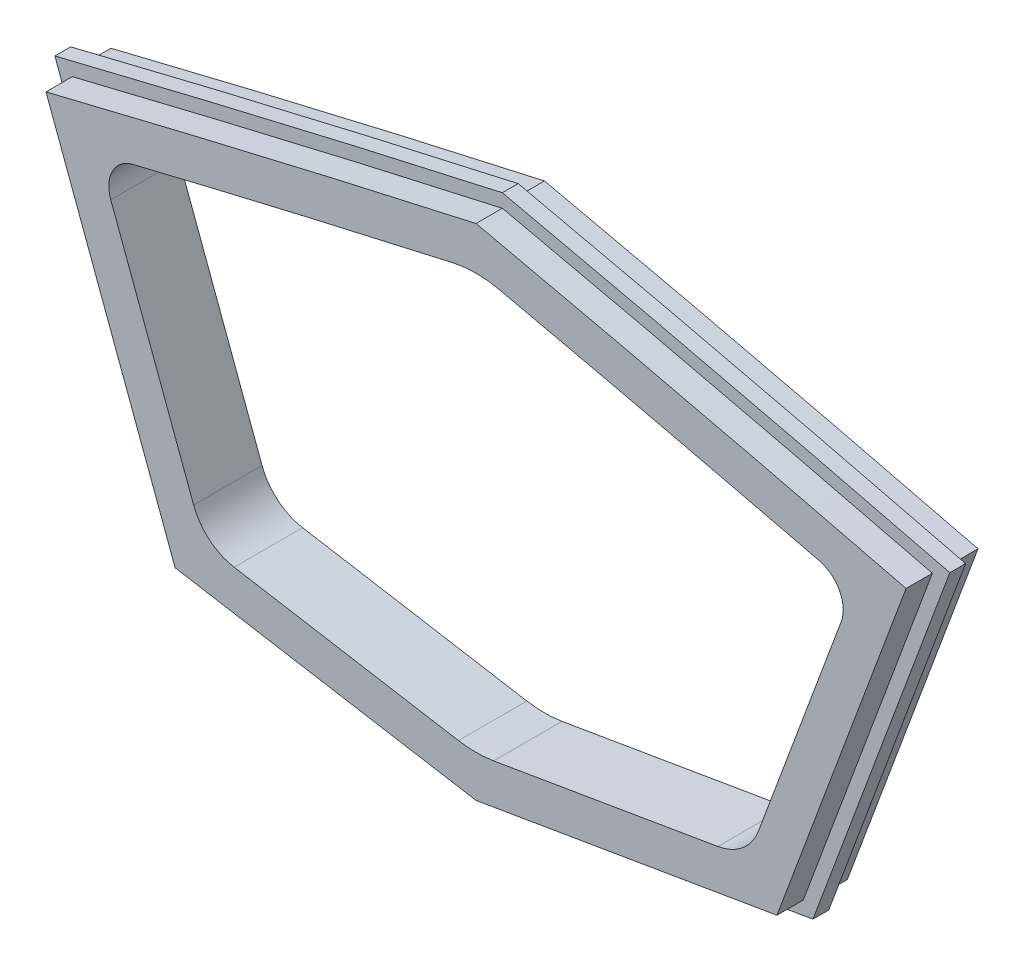
SolidWorks part; units mm, degrees
material "ABS"
ref_plane "Front Plane" through (0, 0, 0) normal (0, 0, 1) x (1, 0, 0)
ref_plane "Top Plane" through (0, 0, 0) normal (0, 1, 0) x (1, 0, 0)
ref_plane "Right Plane" through (0, 0, 0) normal (1, 0, 0) x (0, 0, -1)
sketch "Sketch1" plane through (0, 0, 0) normal (0, 0, 1) x (1, 0, 0)
  line L0 (51.6321, -61.1055) -> (71.7233, -7.0229)
  line L1 (-71.7233, -7.0229) -> (-51.6321, -61.1055)
  line L2 (-51.6321, -61.1055) -> (0, -69.8574)
  line L3 (0, -69.8574) -> (51.6321, -61.1055)
  line L8 (58.9956, -70) -> (85, 0.0001)
  line L9 (0, -80) -> (58.9956, -70)
  line L10 (-58.9956, -70) -> (0, -80)
  line L11 (-85, 0.0001) -> (-58.9956, -70)
  spline S0 degree 1 poles (71.7233, -7.0229) (0, 9.7572) knots 0 0 1 1 construction
  spline S1 degree 1 poles (0, 9.7572) (-71.7233, -7.0229) knots 0 0 1 1 construction
  spline S4 degree 3 poles (0, 19.9999) (-28.4207, 13.7115) (-56.7505, 7.0175) (-85, 0.0001) knots 0 0 0 0 1 1 1 1
  spline S5 degree 3 poles (85, 0.0001) (56.7505, 7.0175) (28.4208, 13.7115) (0, 19.9999) knots 0 0 0 0 1 1 1 1
  spline S6 degree 3 poles (71.7233, -7.0229) (65.7602, -5.5606) (53.8262, -2.6655) (35.9064, 1.5822) (17.9654, 5.7307) (5.9913, 8.427) (0, 9.7572) knots 0.128509 0.128509 0.128509 0.128509 0.340026 0.551543 0.76306 0.974577 0.974577 0.974577 0.974577
  spline S7 degree 3 poles (0, 9.7572) (-5.9913, 8.427) (-17.9654, 5.7308) (-35.9064, 1.5822) (-53.8262, -2.6654) (-65.7603, -5.5605) (-71.7233, -7.0229) knots 0.025423 0.025423 0.025423 0.025423 0.23694 0.448457 0.659974 0.871491 0.871491 0.871491 0.871491
  dimension "D2" = 10
extrude "Boss-Extrude1" add sketch "Sketch1" along normal blind 3
fillet "Fillet1" radius 20 2 edges at (0, -69.8574, 1.5) (0, 9.7572, 1.5)
fillet "Fillet2" radius 10 2 edges at (51.6321, -61.1055, 1.5) (-51.6321, -61.1055, 1.5)
fillet "Fillet3" radius 6 2 edges at (71.7233, -7.0229, 1.5) (-71.7233, -7.0229, 1.5)
sketch "Sketch2" plane through (0, 0, 3) normal (0, 0, 1) x (1, 0, 0)
  line L4 (-69.376, -13.3415) -> (-53.6427, -55.6934) construction
  line L5 (-45.9398, -62.0704) -> (-3.3424, -69.2908) construction
  line L6 (3.3424, -69.2908) -> (45.9398, -62.0704) construction
  line L7 (53.6427, -55.6934) -> (69.376, -13.3416) construction
  line L8 (-81.682, -1.7527) -> (-57.1548, -67.7764)
  line L9 (-57.1548, -67.7764) -> (0, -77.4643)
  line L10 (0, -77.4643) -> (57.1548, -67.7764)
  line L11 (57.1548, -67.7764) -> (81.6819, -1.7527)
  line L12 (-81.682, -1.7527) -> (-57.1548, -67.7764)
  line L13 (-57.1548, -67.7764) -> (0, -77.4643)
  line L14 (0, -77.4643) -> (57.1548, -67.7764)
  line L15 (57.1548, -67.7764) -> (81.6819, -1.7527)
  line L16 (-69.376, -13.3415) -> (-53.6427, -55.6934)
  line L17 (-45.9398, -62.0704) -> (-3.3424, -69.2908)
  line L18 (3.3424, -69.2908) -> (45.9398, -62.0704)
  line L19 (53.6427, -55.6934) -> (69.376, -13.3416)
  arc A1 (-65.1699, -5.4221) -> (-69.376, -13.3415) centre (-63.7516, -11.2521) ccw construction
  arc A2 (-53.6427, -55.6934) -> (-45.9398, -62.0704) centre (-44.2686, -52.211) ccw construction
  arc A3 (-3.3424, -69.2908) -> (3.3424, -69.2908) centre (0, -49.5721) ccw construction
  arc A4 (45.9398, -62.0704) -> (53.6427, -55.6934) centre (44.2686, -52.211) ccw construction
  arc A5 (69.376, -13.3416) -> (65.1699, -5.4222) centre (63.7515, -11.2521) ccw construction
  arc A6 (4.3632, 8.7852) -> (-4.3632, 8.7852) centre (0, -10.7331) ccw construction
  arc A7 (-65.1699, -5.4221) -> (-69.376, -13.3415) centre (-63.7516, -11.2521) ccw
  arc A8 (-53.6427, -55.6934) -> (-45.9398, -62.0704) centre (-44.2686, -52.211) ccw
  arc A9 (-3.3424, -69.2908) -> (3.3424, -69.2908) centre (0, -49.5721) ccw
  arc A10 (45.9398, -62.0704) -> (53.6427, -55.6934) centre (44.2686, -52.211) ccw
  arc A11 (69.376, -13.3416) -> (65.1699, -5.4222) centre (63.7515, -11.2521) ccw
  arc A12 (4.3632, 8.7852) -> (-4.3632, 8.7852) centre (0, -10.7331) ccw
  spline S3 degree 3 poles (2856.2231, -710.7914) (1223.1942, 104.564) (579.2853, 143.8341) (-35.9064, 1.5822) (-1030.2564, -234.1159) (-1933.2229, -901.7007) (1099.9889, 2490.3845) knots -21.098589 -21.098589 -21.098589 -21.098589 0.23694 0.448457 0.659974 35.447452 35.447452 35.447452 35.447452 only from (-4.3632, 8.7852) to (-65.1699, -5.4221) construction
  spline S4 degree 3 poles (3213.9817, 1579.7272) (901.2899, -2961.498) (-164.1911, 3027.1999) (-2889.2123, -2307.1163) knots -36.346529 -36.346529 -36.346529 -36.346529 30.527536 30.527536 30.527536 30.527536 only from (81.6819, -1.7527) to (0, 17.4394)
  spline S5 degree 3 poles (2884.6712, -2310.9837) (170.5811, 3032.8885) (-910.5565, -2969.0724) (-3206.0132, 1587.7256) knots -29.53804 -29.53804 -29.53804 -29.53804 37.373414 37.373414 37.373414 37.373414 only from (0, 17.4394) to (-81.682, -1.7527)
  spline S6 degree 3 poles (81.6819, -1.7527) (54.5322, 4.9703) (27.3082, 11.392) (0, 17.4394) knots 0 0 0 0 1 1 1 1
  spline S7 degree 3 poles (0, 17.4394) (-27.3081, 11.392) (-54.5323, 4.9703) (-81.682, -1.7527) knots 0 0 0 0 1 1 1 1
  spline S8 degree 3 poles (-1113.3341, 2488.3803) (1932.0695, -900.8143) (1029.5812, -233.957) (35.9064, 1.5822) (-580.0364, 144.0085) (-1224.8367, 104.4791) (-2854.4298, -715.5725) knots -34.423595 -34.423595 -34.423595 -34.423595 0.340026 0.551543 0.76306 22.125182 22.125182 22.125182 22.125182 only from (65.1699, -5.4222) to (4.3632, 8.7852) construction
  spline S9 degree 3 poles (-4.3632, 8.7852) (-8.8983, 7.7714) (-19.4173, 5.395) (-35.9064, 1.5822) (-51.6385, -2.1469) (-61.389, -4.5023) (-65.1699, -5.4221) knots 0.076777 0.076777 0.076777 0.076777 0.23694 0.448457 0.659974 0.794023 0.794023 0.794023 0.794023
  spline S10 degree 3 poles (65.1699, -5.4222) (61.389, -4.5024) (51.6385, -2.1469) (35.9064, 1.5822) (19.4173, 5.395) (8.8983, 7.7714) (4.3632, 8.7852) knots 0.205976 0.205976 0.205976 0.205976 0.340026 0.551543 0.76306 0.923223 0.923223 0.923223 0.923223
  dimension "D1" = 2.5
extrude "Boss-Extrude2" add sketch "Sketch2" along normal blind 5
sketch "Sketch3" plane through (0, 0, 0) normal (0, 0, -1) x (-1, 0, 0)
  line L0 (69.376, -13.3415) -> (53.6427, -55.6934) construction
  line L1 (45.9398, -62.0704) -> (3.3424, -69.2908) construction
  line L2 (-3.3424, -69.2908) -> (-45.9398, -62.0704) construction
  line L3 (-53.6427, -55.6934) -> (-69.376, -13.3416) construction
  line L12 (57.5229, -68.2211) -> (82.3456, -1.4019)
  line L13 (0, -77.9715) -> (57.5229, -68.2211)
  line L14 (-57.5229, -68.2211) -> (0, -77.9715)
  line L15 (-82.3456, -1.402) -> (-57.5229, -68.2211)
  line L16 (57.5229, -68.2211) -> (82.3456, -1.4019)
  line L17 (0, -77.9715) -> (57.5229, -68.2211)
  line L18 (-57.5229, -68.2211) -> (0, -77.9715)
  line L19 (-82.3456, -1.402) -> (-57.5229, -68.2211)
  line L20 (-53.6427, -55.6934) -> (-69.376, -13.3416)
  line L21 (-3.3424, -69.2908) -> (-45.9398, -62.0704)
  line L22 (45.9398, -62.0704) -> (3.3424, -69.2908)
  line L23 (69.376, -13.3415) -> (53.6427, -55.6934)
  arc A0 (4.3632, 8.7852) -> (-4.3632, 8.7852) centre (0, -10.7331) ccw construction
  arc A1 (69.376, -13.3415) -> (65.1699, -5.4221) centre (63.7516, -11.2521) ccw construction
  arc A2 (45.9398, -62.0704) -> (53.6427, -55.6934) centre (44.2686, -52.211) ccw construction
  arc A3 (-3.3424, -69.2908) -> (3.3424, -69.2908) centre (0, -49.5721) ccw construction
  arc A4 (-53.6427, -55.6934) -> (-45.9398, -62.0704) centre (-44.2686, -52.211) ccw construction
  arc A5 (-65.1699, -5.4222) -> (-69.376, -13.3416) centre (-63.7515, -11.2521) ccw construction
  arc A6 (-65.1699, -5.4222) -> (-69.376, -13.3416) centre (-63.7515, -11.2521) ccw
  arc A7 (-53.6427, -55.6934) -> (-45.9398, -62.0704) centre (-44.2686, -52.211) ccw
  arc A8 (-3.3424, -69.2908) -> (3.3424, -69.2908) centre (0, -49.5721) ccw
  arc A9 (45.9398, -62.0704) -> (53.6427, -55.6934) centre (44.2686, -52.211) ccw
  arc A10 (69.376, -13.3415) -> (65.1699, -5.4221) centre (63.7516, -11.2521) ccw
  arc A11 (4.3632, 8.7852) -> (-4.3632, 8.7852) centre (0, -10.7331) ccw
  spline S0 degree 3 poles (-1947.6207, -293.2287) (-956.0423, 113.109) (-452.1928, 114.4463) (35.9064, 1.5822) (950.4936, -215.2091) (1786.9263, -796.7733) (-436.8515, 1741.9638) knots -16.603487 -16.603487 -16.603487 -16.603487 0.23694 0.448457 0.659974 32.623003 32.623003 32.623003 32.623003 only from (4.3632, 8.7852) to (65.1699, -5.4221) construction
  spline S1 degree 3 poles (448.3337, 1741.5955) (-1786.0704, -796.1529) (-949.9918, -215.0912) (-35.9064, 1.5822) (452.7161, 114.5678) (957.1703, 113.1138) (1947.0313, -295.4162) knots -31.605284 -31.605284 -31.605284 -31.605284 0.340026 0.551543 0.76306 17.622017 17.622017 17.622017 17.622017 only from (-65.1699, -5.4222) to (-4.3632, 8.7852) construction
  spline S2 degree 3 poles (-65.1699, -5.4222) (-61.389, -4.5024) (-51.6385, -2.1469) (-35.9064, 1.5822) (-19.4173, 5.395) (-8.8983, 7.7714) (-4.3632, 8.7852) knots 0.205976 0.205976 0.205976 0.205976 0.340026 0.551543 0.76306 0.923223 0.923223 0.923223 0.923223
  spline S3 degree 3 poles (4.3632, 8.7852) (8.8983, 7.7714) (19.4173, 5.395) (35.9064, 1.5822) (51.6385, -2.1469) (61.389, -4.5023) (65.1699, -5.4221) knots 0.076777 0.076777 0.076777 0.076777 0.23694 0.448457 0.659974 0.794023 0.794023 0.794023 0.794023
  spline S6 degree 3 poles (4008.5596, -5105.7117) (-17.453, 6123.7898) (-852.3779, -6105.4551) (-4249.6593, 4431.8099) knots -41.130804 -41.130804 -41.130804 -41.130804 50.462428 50.462428 50.462428 50.462428 only from (0.0002, 17.9394) to (-82.3456, -1.402)
  spline S7 degree 3 poles (4224.2214, 4447.9687) (875.8829, -6119.6495) (-0.9348, 6134.8849) (-3994.1278, -5113.8686) knots -49.489078 -49.489078 -49.489078 -49.489078 42.142383 42.142383 42.142383 42.142383 only from (82.3456, -1.4019) to (0.0002, 17.9394)
  spline S8 degree 3 poles (0.0002, 17.9394) (-27.5313, 11.8519) (-54.9768, 5.379) (-82.3456, -1.402) knots -0.075105 -0.075105 -0.075105 -0.075105 1.011252 1.011252 1.011252 1.011252
  spline S9 degree 3 poles (82.3456, -1.4019) (54.977, 5.379) (27.5316, 11.8519) (0.0002, 17.9394) knots -0.011247 -0.011247 -0.011247 -0.011247 1.075105 1.075105 1.075105 1.075105
  dimension "D2" = 0
extrude "Boss-Extrude3" add sketch "Sketch3" along normal blind 5
